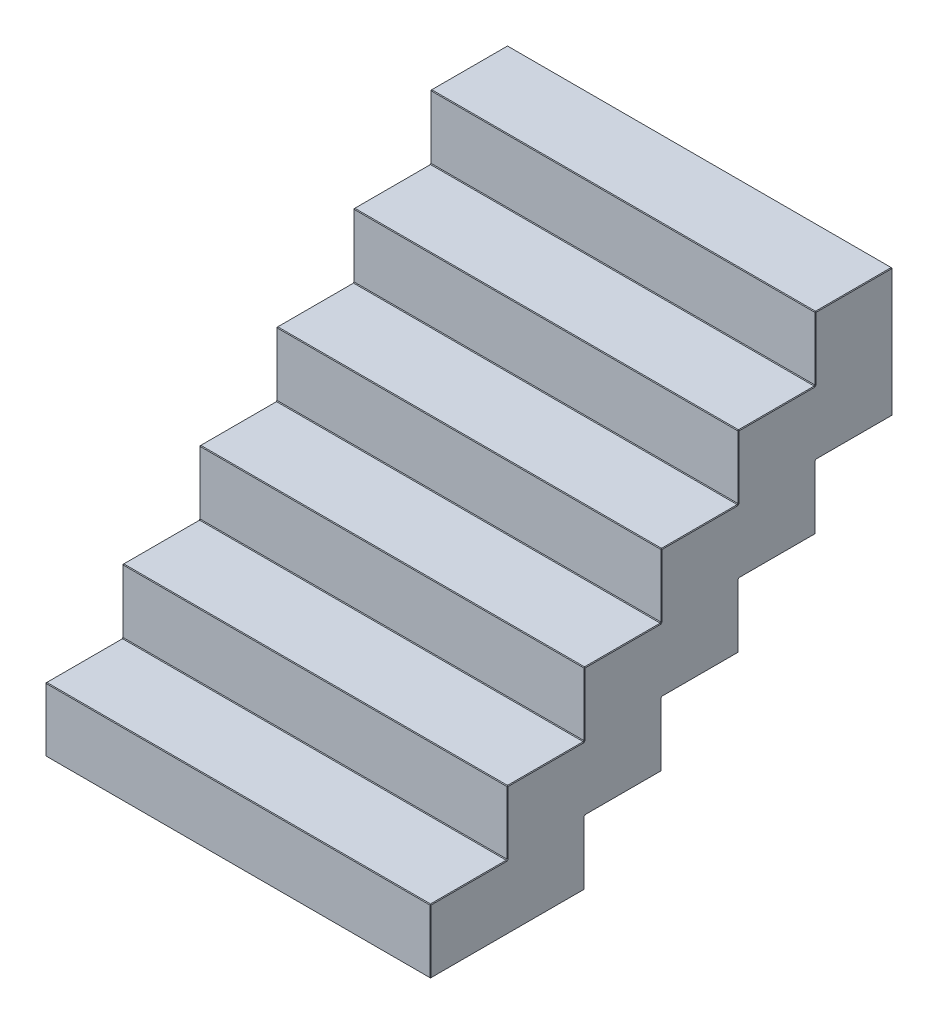
SolidWorks part; units mm, degrees
material "AISI 1020"
ref_plane "Front Plane" through (0, 0, 0) normal (0, 0, 1) x (1, 0, 0)
ref_plane "Top Plane" through (0, 0, 0) normal (0, 1, 0) x (1, 0, 0)
ref_plane "Right Plane" through (0, 0, 0) normal (1, 0, 0) x (0, 0, -1)
sketch "Sketch3" plane through (0, 0, 0) normal (1, 0, 0) x (0, 0, -1)
  line L0 (0, 0) -> (0, 254)
  line L1 (0, 254) -> (304.8, 254)
  line L2 (304.8, 254) -> (304.8, 508)
  line L3 (304.8, 508) -> (609.6, 508)
  line L4 (609.6, 508) -> (609.6, 762)
  line L5 (609.6, 762) -> (914.4, 762)
  line L6 (914.4, 762) -> (914.4, 1016)
  line L7 (914.4, 1016) -> (1219.2, 1016)
  line L8 (1219.2, 1016) -> (1219.2, 1270)
  line L9 (1219.2, 1270) -> (1524, 1270)
  line L10 (1524, 1270) -> (1524, 1524)
  line L11 (1524, 1524) -> (1828.8, 1524)
  line L21 (609.6, 0) -> (0, 0)
  line L22 (609.6, 0) -> (609.6, 254)
  line L23 (609.6, 254) -> (914.4, 254)
  line L24 (914.4, 254) -> (914.4, 508)
  line L25 (914.4, 508) -> (1219.2, 508)
  line L26 (1219.2, 508) -> (1219.2, 762)
  line L27 (1219.2, 762) -> (1524, 762)
  line L28 (1524, 762) -> (1524, 1016)
  line L29 (1524, 1016) -> (1828.8, 1016)
  line L30 (1828.8, 1016) -> (1828.8, 1270)
  line L38 (1828.8, 1524) -> (1828.8, 1270)
  dimension "D1" = 254
  dimension "D2" = 254
  dimension "D3" = 254
  dimension "D4" = 254
  dimension "D5" = 254
  dimension "D10" = 254
  dimension "D12" = 304.8
  dimension "D13" = 304.8
  dimension "D14" = 304.8
  dimension "D15" = 304.8
  dimension "D16" = 304.8
  dimension "D17" = 304.8
extrude "Boss-Extrude2" add sketch "Sketch3" along normal blind 1524
chamfer "Chamfer1" distance 2.54 angle 45 66 edges at (762, 508, -609.6) (762, 508, -304.8) (762, 0, -609.6) (762, 508, -914.4) (762, 1524, -1828.8) (762, 1524, -1524) (762, 1270, -1524) (762, 1270, -1219.2) (762, 1016, -1219.2) (762, 1016, -914.4) (762, 762, -914.4) (762, 762, -609.6) (762, 254, -304.8) (762, 254, 0) (762, 0, 0) (762, 254, -609.6) (762, 254, -914.4) (762, 508, -1219.2) (762, 762, -1219.2) (762, 762, -1524) (762, 1016, -1524) (0, 127, -609.6) (0, 254, -762) (0, 381, -914.4) (0, 508, -1066.8) (0, 635, -1219.2) (0, 762, -1371.6) (0, 889, -1524) (0, 1016, -1676.4) (0, 0, -304.8) (0, 127, 0) (0, 254, -152.4) (0, 381, -304.8) (0, 508, -457.2) (0, 635, -609.6) (0, 762, -762) (0, 889, -914.4) (0, 1016, -1066.8) (0, 1143, -1219.2) (0, 1270, -1371.6) (0, 1397, -1524) (0, 1524, -1676.4) (0, 1270, -1828.8) (762, 1016, -1828.8) (1524, 127, 0) (1524, 254, -152.4) (1524, 381, -304.8) (1524, 508, -457.2) (1524, 635, -609.6) (1524, 762, -762) (1524, 889, -914.4) (1524, 1016, -1066.8) (1524, 1143, -1219.2) (1524, 1270, -1371.6) (1524, 1397, -1524) (1524, 1524, -1676.4) (1524, 1270, -1828.8) (1524, 1016, -1676.4) (1524, 889, -1524) (1524, 762, -1371.6) (1524, 635, -1219.2) (1524, 508, -1066.8) (1524, 381, -914.4) (1524, 254, -762) (1524, 127, -609.6) (1524, 0, -304.8)
